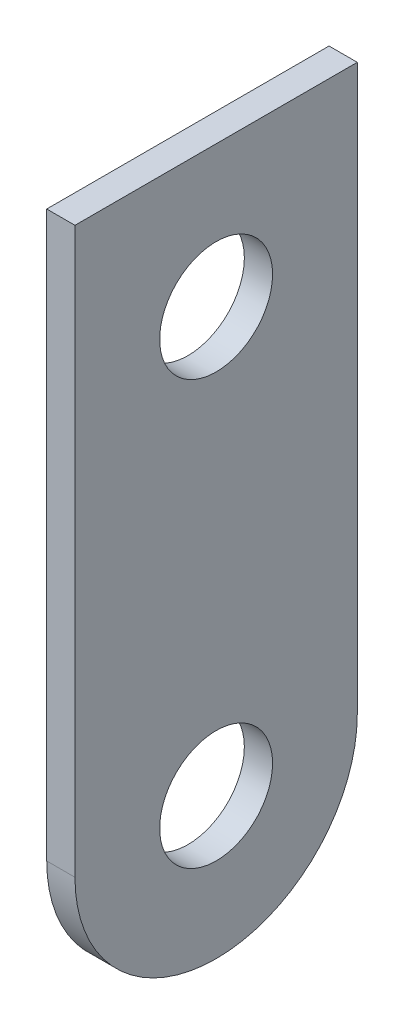
SolidWorks part; units mm, degrees
material "AISI 1020 Steel, Cold Rolled"
ref_plane "Front Plane" through (0, 0, 0) normal (0, 0, 1) x (1, 0, 0)
ref_plane "Top Plane" through (0, 0, 0) normal (0, 1, 0) x (1, 0, 0)
ref_plane "Right Plane" through (0, 0, 0) normal (1, 0, 0) x (0, 0, -1)
sketch "Sketch1" plane through (0, 0, 0) normal (1, 0, 0) x (0, 0, -1)
  line L2 (50, 150) -> (0, 150)
  line L6 (0, 50) -> (0, 150)
  line L7 (50, 50) -> (50, 150)
  circle A3 centre (25, 50) radius 10
  circle A4 centre (25, 125) radius 10
  arc A5 (0, 50) -> (50, 50) centre (25, 50) ccw
extrude "Boss-Extrude1" add sketch "Sketch1" along normal blind 5
